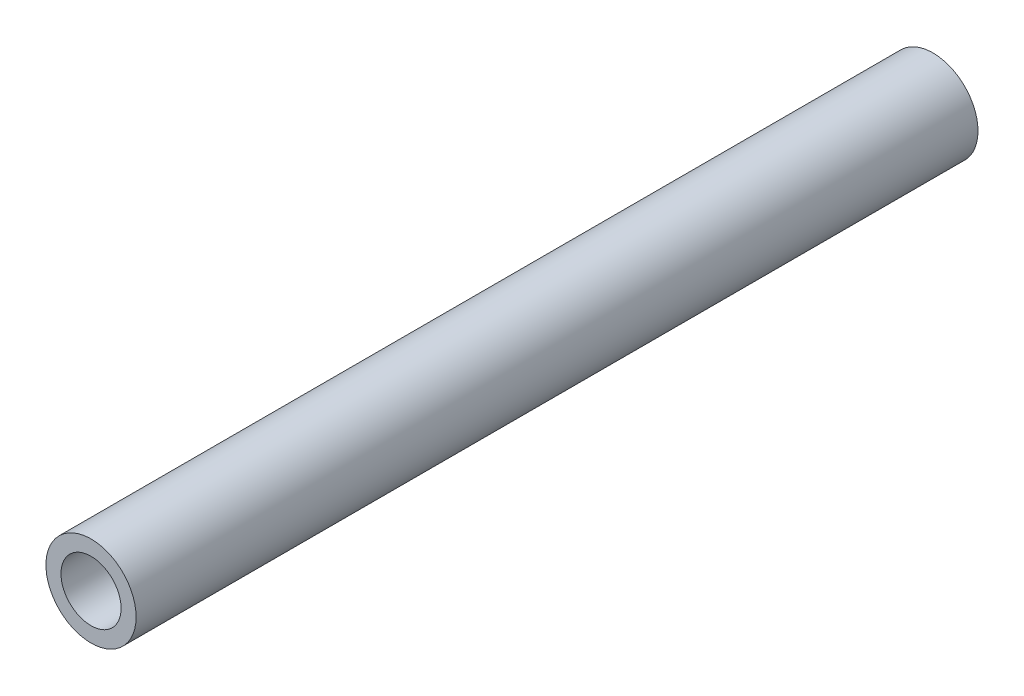
SolidWorks part; units mm, degrees
material "AISI 4140 Steel, quenched & tempered"
ref_plane "Front Plane" through (0, 0, 0) normal (1, 0, 0) x (0, 1, 0)
ref_plane "Top Plane" through (0, 0, 0) normal (0, 0, 1) x (0, 1, 0)
ref_plane "Right Plane" through (0, 0, 0) normal (0, 1, 0) x (-1, 0, 0)
sketch "Sketch1" plane through (0, 0, 0) normal (0, 0, 1) x (0, 1, 0)
  circle A0 centre (0, 0) radius 15
  circle A1 centre (0, 0) radius 10
  dimension "D1" = 20
  dimension "D2" = 30
extrude "Boss-Extrude1" add sketch "Sketch1" against normal mid plane 280
